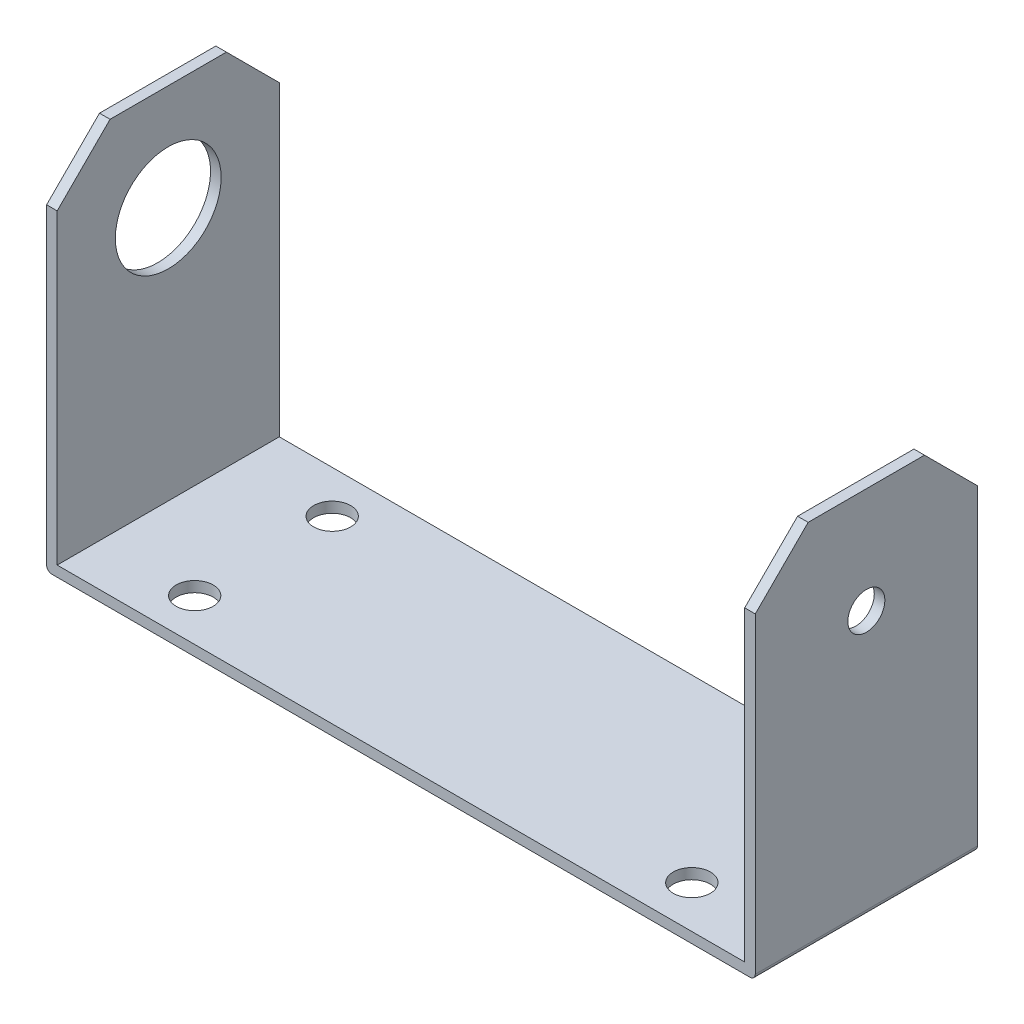
SolidWorks part; units mm, degrees
ref_plane "前视基准面" through (0, 0, 0) normal (0, 0, 1) x (1, 0, 0)
ref_plane "上视基准面" through (0, 0, 0) normal (0, 1, 0) x (1, 0, 0)
ref_plane "右视基准面" through (0, 0, 0) normal (1, 0, 0) x (0, 0, -1)
sketch "草图1" plane through (0, 0, 0) normal (0, 1, 0) x (1, 0, 0)
  line L0 (0, 0) -> (-67, 0)
  line L1 (-67, 0) -> (-67, 21)
  line L2 (-67, 21) -> (0, 21)
  line L3 (0, 21) -> (0, 0)
  dimension "D1" = 67
  dimension "D2" = 21
extrude "凸台-拉伸1" add sketch "草图1" along normal blind 35
shell "抽壳1" thickness 1
fillet "圆角2" radius 0.5 2 edges at (0, 0, -10.5) (-67, 0, -10.5)
chamfer "倒角1" distance 5 distance2 5 4 edges at (-0.5, 35, -21) (-0.5, 35, 0) (-66.5, 35, -21) (-66.5, 35, 0)
hole_wizard "Ø3.5 (3.5) 直径槽口1" positions "草图2" profile "草图4" size "Ø3.5" standard "GB" slot yes end condition through all
sketch "草图2" plane through (0, 1, 0) normal (0, 1, 0) x (1, 0, 0)
  line L0 (-1, 21) -> (-66, 21) construction
  line L1 (-66, 0) -> (-1, 0) construction
  line L2 (-33.5, 21) -> (-33.5, 0) construction
  point P0 (-57, 17)
  point P2 (-10, 17)
  point P4 (-10, 4)
  point P6 (-57, 4)
  dimension "D1" = 4
  dimension "D2" = 4
  dimension "D3" = 23.5
  dimension "D4" = 23.5
sketch "草图4" plane through (-57, 1, -17) normal (1, 0, 0) x (0, 0, 1)
  line L0 (0, 0) -> (0, 1)
  line L1 (0, 1) -> (1.75, 1)
  line L2 (1.75, 1) -> (1.75, 0)
  line L5 (1.75, 0) -> (0, 0)
  line L11 (0, -6.35) -> (0, 107.95) construction
  dimension "通孔孔直径" = 3.5
  dimension "通孔孔深度" = 1
hole_wizard "Ø10.0 (10) 直径槽口1" positions "草图5" profile "草图6" size "Ø10.0" standard "GB"
sketch "草图5" plane through (-67, 0, 0) normal (-1, 0, 0) x (0, 0, 1)
  line L0 (-16, 35) -> (-5, 35) construction
  line L1 (-21, 30) -> (-21, 0.5) construction
  point P12 (-10.5, 25)
  dimension "D1" = 10
  dimension "D2" = 10.5
sketch "草图6" plane through (-67, 25, -10.5) normal (0, 1, 0) x (0, 0, 1)
  line L0 (0, 0) -> (0, 1)
  line L1 (0, 1) -> (5, 1)
  line L2 (5, 1) -> (5, 0)
  line L5 (5, 0) -> (0, 0)
  line L11 (0, -6.35) -> (0, 107.95) construction
  dimension "通孔孔直径" = 10
  dimension "通孔孔深度" = 1
hole_wizard "Ø3.5 (3.5) 直径槽口2" positions "草图7" profile "草图8" size "Ø3.5" standard "GB" slot yes end condition up to next
sketch "草图7" plane through (0, 0, 0) normal (1, 0, 0) x (0, 0, -1)
  line L0 (5, 35) -> (16, 35) construction
  point P0 (10.5, 25)
  point P6 (10.5, 35)
  dimension "D1" = 10
sketch "草图8" plane through (0, 25, -10.5) normal (0, 1, 0) x (0, 0, -1)
  line L0 (0, 0) -> (0, 1)
  line L1 (0, 1) -> (1.75, 1)
  line L2 (1.75, 1) -> (1.75, 0)
  line L5 (1.75, 0) -> (0, 0)
  line L11 (0, -6.35) -> (0, 107.95) construction
  dimension "通孔孔直径" = 3.5
  dimension "通孔孔深度" = 1
